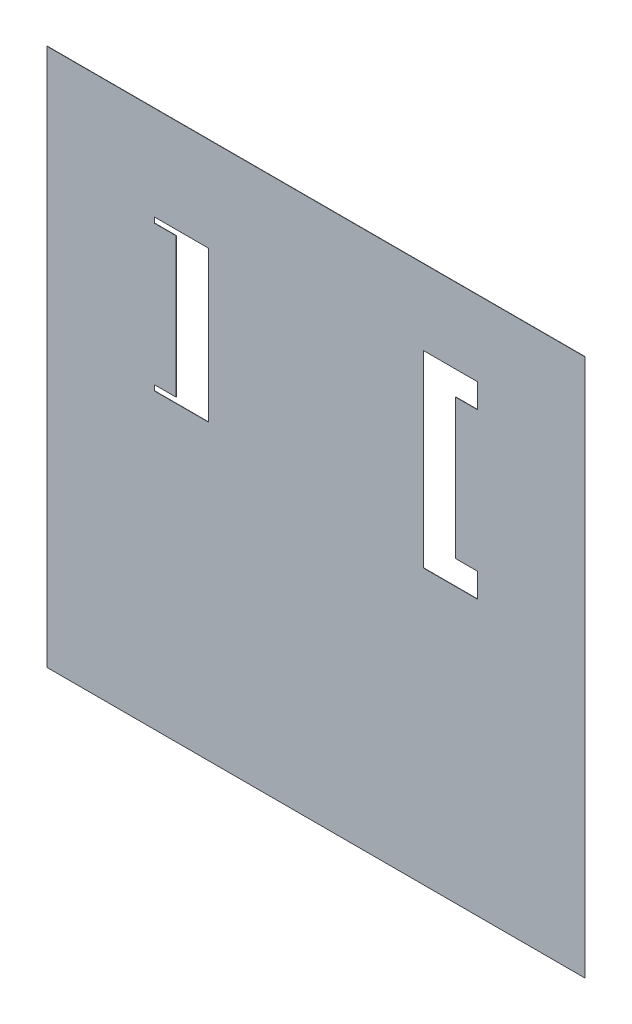
SolidWorks part; units mm, degrees
material "Aluminum Bronze"
ref_plane "Front Plane" through (0, 0, 0) normal (0, 0, 1) x (1, 0, 0)
ref_plane "Top Plane" through (0, 0, 0) normal (0, 1, 0) x (1, 0, 0)
ref_plane "Right Plane" through (0, 0, 0) normal (1, 0, 0) x (0, 0, -1)
sketch "Sketch1" plane through (0, 0, 0) normal (0, 0, 1) x (1, 0, 0)
  line L1 (0, 0) -> (25.4, 0)
  line L2 (0, 0) -> (0, 25.4)
  line L3 (0, 25.4) -> (25.4, 25.4)
  line L4 (25.4, 0) -> (25.4, 25.4)
  dimension "D1" = 25.4
  dimension "D2" = 25.4
extrude "Boss-Extrude1" add sketch "Sketch1" along normal blind 0.0127
sketch "Sketch2" plane through (0, 0, 0.0127) normal (0, 0, 1) x (1, 0, 0)
  line L0 (25.4, 25.4) -> (0, 25.4) construction
  line L1 (5.08, 20.955) -> (7.62, 20.955)
  line L2 (5.08, 20.955) -> (5.08, 20.701)
  line L3 (5.08, 13.843) -> (7.62, 13.843)
  line L4 (7.62, 20.955) -> (7.62, 13.843)
  line L5 (17.78, 21.844) -> (20.32, 21.844)
  line L6 (17.78, 21.844) -> (17.78, 12.954)
  line L7 (17.78, 12.954) -> (20.32, 12.954)
  line L8 (20.32, 21.844) -> (20.32, 20.701)
  line L9 (5.08, 14.097) -> (5.08, 13.843)
  line L10 (5.08, 14.097) -> (6.096, 14.097)
  line L11 (20.32, 14.097) -> (20.32, 12.954)
  line L12 (5.08, 20.701) -> (6.096, 20.701)
  line L13 (6.096, 14.097) -> (6.096, 20.701)
  line L14 (20.32, 14.097) -> (19.304, 14.097)
  line L16 (20.32, 20.701) -> (19.304, 20.701)
  line L17 (19.304, 14.097) -> (19.304, 20.701)
  point P8 (6.35, 20.955)
  point P11 (12.7, 25.4)
  point P12 (6.35, 13.843)
  point P13 (19.05, 12.954)
  point P22 (19.304, 17.399)
  point P23 (17.78, 17.399)
  point P24 (6.096, 17.399)
  point P25 (7.62, 17.399)
  dimension "D1" = 2.54
  dimension "D2" = 2.54
  dimension "D3" = 6.35
  dimension "D4" = 12.7
  dimension "D5" = 7.112
  dimension "D6" = 8.89
  dimension "D7" = 3.556
  dimension "D8" = 4.445
  dimension "D9" = 0
  dimension "D10" = 6.604
  dimension "D11" = 1.016
  dimension "D12" = 0
  dimension "D13" = 6.604
  dimension "D14" = 1.016
extrude "Cut-Extrude8" cut sketch "Sketch2" along normal blind 3.556 and the other way through all
